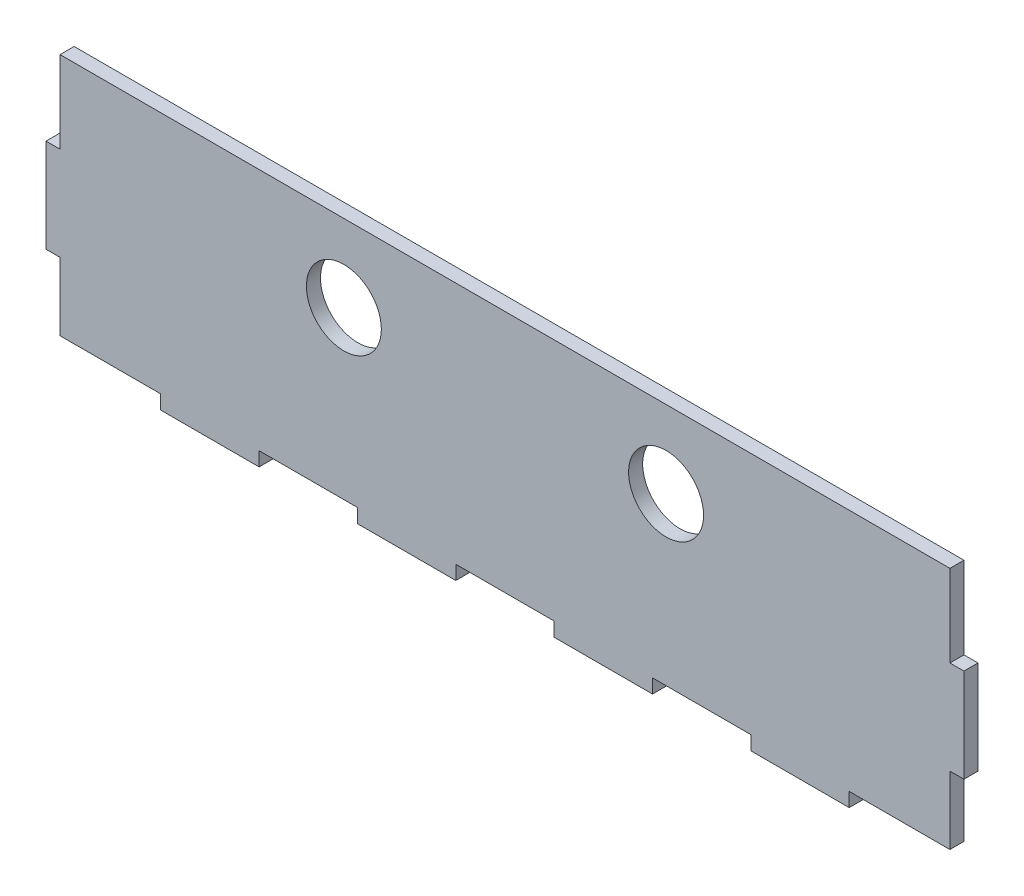
SolidWorks part; units mm, degrees
ref_plane "Front Plane" through (0, 0, 0) normal (0, 0, 1) x (1, 0, 0)
ref_plane "Top Plane" through (0, 0, 0) normal (0, 1, 0) x (1, 0, 0)
ref_plane "Right Plane" through (0, 0, 0) normal (1, 0, 0) x (0, 0, -1)
sketch "Sketch1" plane through (0, 0, 0) normal (0, 0, 1) x (1, 0, 0)
  line L0 (0, -24.5) -> (10.5, -24.5)
  line L1 (-98, -27.5) -> (98, -27.5)
  line L2 (-98, -27.5) -> (-98, 27.5)
  line L3 (-98, 27.5) -> (98, 27.5)
  line L4 (98, -27.5) -> (98, 27.5)
  line L5 (-98, -27.5) -> (98, 27.5) construction
  line L6 (-98, 27.5) -> (98, -27.5) construction
  line L7 (10.5, -24.5) -> (10.5, -27.5)
  line L8 (10.5, -27.5) -> (31.5, -27.5)
  line L9 (31.5, -27.5) -> (31.5, -24.5)
  line L10 (31.5, -24.5) -> (52.5, -24.5)
  line L11 (52.5, -24.5) -> (52.5, -27.5)
  line L12 (52.5, -27.5) -> (73.5, -27.5)
  line L13 (73.5, -27.5) -> (73.5, -24.5)
  line L14 (73.5, -24.5) -> (98, -24.5)
  line L15 (0, -24.5) -> (-10.5, -24.5)
  line L16 (-10.5, -24.5) -> (-10.5, -27.5)
  line L17 (-10.5, -27.5) -> (-31.5, -27.5)
  line L18 (-31.5, -27.5) -> (-31.5, -24.5)
  line L19 (-31.5, -24.5) -> (-52.5, -24.5)
  line L20 (-52.5, -24.5) -> (-52.5, -27.5)
  line L21 (-52.5, -27.5) -> (-73.5, -27.5)
  line L22 (-73.5, -27.5) -> (-73.5, -24.5)
  line L23 (-73.5, -24.5) -> (-98, -24.5)
  line L24 (-98, 10) -> (-95, 10)
  line L25 (-95, 10) -> (-95, 27.5)
  line L26 (-98, -10) -> (-95, -10)
  line L27 (-95, -10) -> (-95, -27.5)
  line L28 (95, 27.5) -> (95, 10)
  line L29 (95, 10) -> (98, 10)
  line L30 (98, 10) -> (98, -10)
  line L31 (98, -10) -> (95, -10)
  line L32 (95, -10) -> (95, -27.5)
  circle A0 centre (-34.4, 11) radius 8
  circle A3 centre (34.4, 11) radius 8
  point P0 (0, 0)
  dimension "D21" = 16
  dimension "D22" = 68.8
  dimension "D24" = 16
  dimension "D29" = 63.6
  dimension "D1" = 55
  dimension "D2" = 196
  dimension "D3" = 10.5
  dimension "D4" = 0
  dimension "D5" = 10.5
  dimension "D6" = 21
  dimension "D7" = 21
  dimension "D8" = 21
  dimension "D9" = 21
  dimension "D10" = 21
  dimension "D11" = 21
  dimension "D12" = 3
  dimension "D13" = 3
  dimension "D14" = 3
  dimension "D15" = 20
  dimension "D16" = 17.5
  dimension "D17" = 3
  dimension "D18" = 3
  dimension "D19" = 3
  dimension "D20" = 3
  dimension "D25" = 16.5
  dimension "D28" = 16.5
  dimension "D30" = 63.6
extrude "Boss-Extrude1" add sketch "Sketch1" along normal blind 3 contours L23 L22 L1 L20 L19 L18 L16 L15 L0 L7 L9 L10 L11 L13 L14 L4 L3 L2
